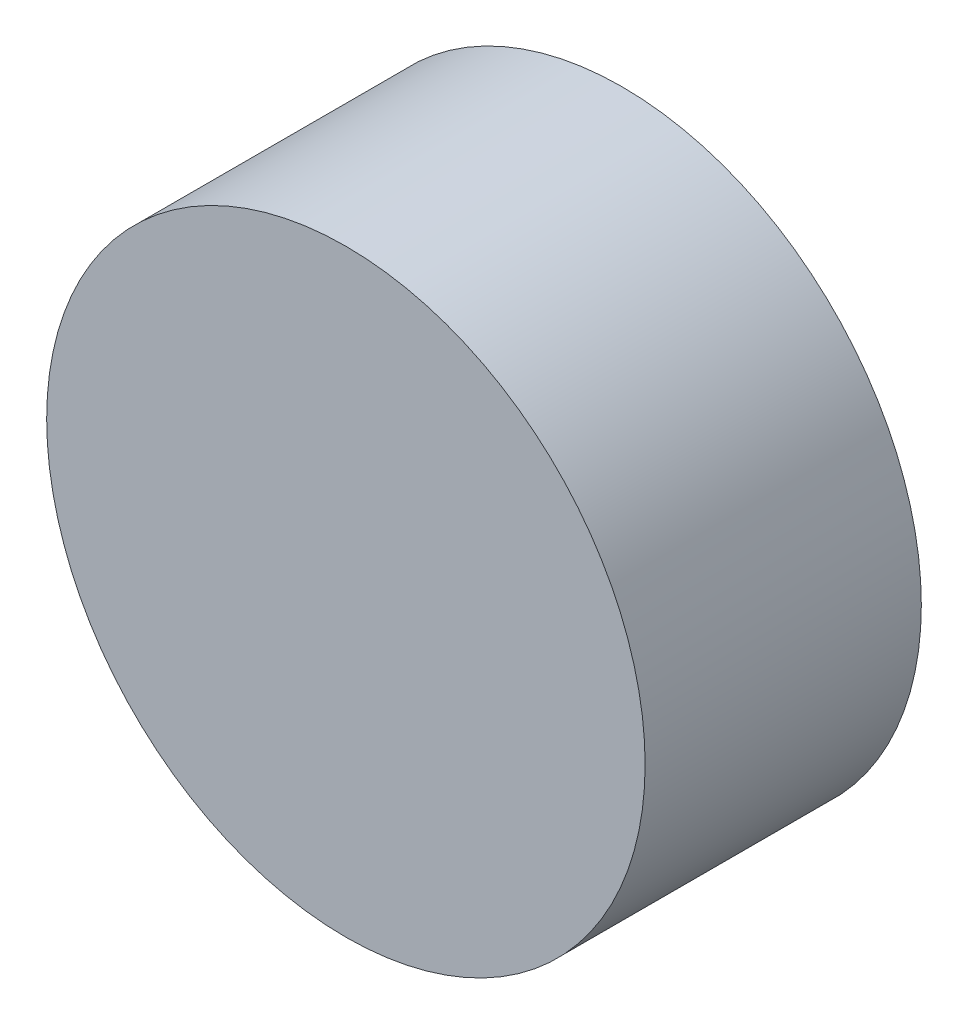
SolidWorks part; units mm, degrees
ref_plane "前视基准面" through (0, 0, 0) normal (0, 0, 1) x (1, 0, 0)
ref_plane "上视基准面" through (0, 0, 0) normal (0, 1, 0) x (1, 0, 0)
ref_plane "右视基准面" through (0, 0, 0) normal (1, 0, 0) x (0, 0, -1)
other "Configuration Table"
sketch "草图1" plane through (0, 0, 0) normal (0, 0, 1) x (1, 0, 0)
  circle A0 centre (0, 0) radius 13
  dimension "diameter" = 26
extrude "Yaw_Motor" add sketch "草图1" along normal blind 12
